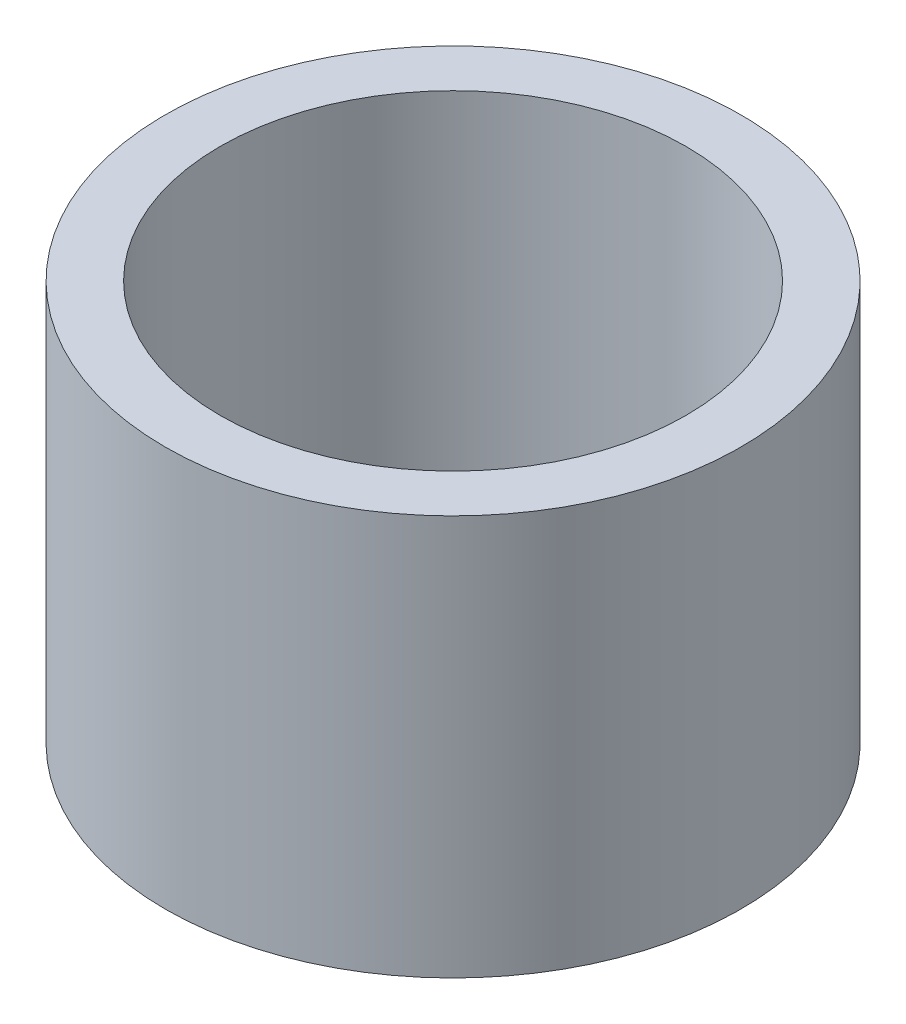
SolidWorks part; units mm, degrees
ref_plane "Front Plane" through (0, 0, 0) normal (0, 0, 1) x (1, 0, 0)
ref_plane "Top Plane" through (0, 0, 0) normal (0, 1, 0) x (1, 0, 0)
ref_plane "Right Plane" through (0, 0, 0) normal (1, 0, 0) x (0, 0, -1)
sketch "Sketch1" plane through (0, 0, 0) normal (0, 1, 0) x (1, 0, 0)
  circle A0 centre (0, 0) radius 10.5
  dimension "D1" = 21
extrude "Boss-Extrude1" add sketch "Sketch1" along normal blind 14.6
sketch "Sketch2" plane through (0, 14.6, 0) normal (0, 1, 0) x (1, 0, 0)
  circle A0 centre (0, 0) radius 8.5
  dimension "D1" = 17
extrude "Cut-Extrude1" cut sketch "Sketch2" against normal through all
